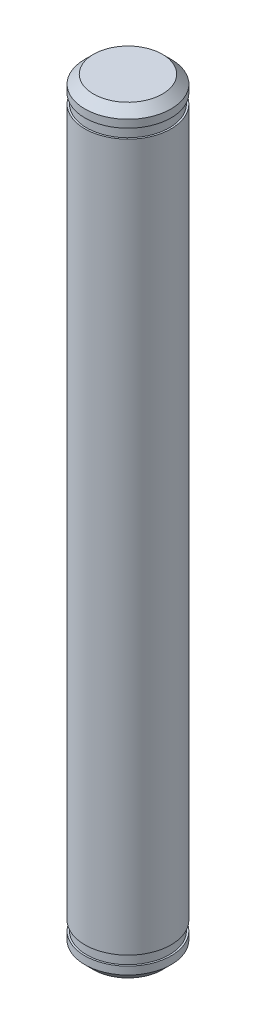
SolidWorks part; units mm, degrees
ref_plane "前视基准面" through (0, 0, 0) normal (0, 0, 1) x (1, 0, 0)
ref_plane "上视基准面" through (0, 0, 0) normal (0, 1, 0) x (1, 0, 0)
ref_plane "右视基准面" through (0, 0, 0) normal (1, 0, 0) x (0, 0, -1)
other "Configuration Table"
sketch "草图1" plane through (0, 0, 0) normal (0, 0, 1) x (1, 0, 0)
  line L0 (0, 61.8249) -> (0, -44.5084) construction
  line L1 (0, 44) -> (5, 44)
  line L2 (5, 44) -> (5, 29)
  line L6 (5, -29) -> (5, -44)
  line L7 (5, -44) -> (0, -44)
  line L8 (0, 0) -> (41.6667, 0) construction
  line L9 (0, 44) -> (0, -44)
  line L10 (5, 29) -> (5, -29)
  dimension "D1" = 5
  dimension "D2" = 5
  dimension "D5" = 88
revolve "旋转1" add sketch "草图1" angle 360 about L9
chamfer "倒角1" distance 1 angle 45 2 edges at (-5, -44, 0) (-5, 44, 0)
ref_plane "基准面1" through (0, 0, 0) normal (0, 1, 0) x (1, 0, 0)
sketch "草图2" plane through (0, 44, 0) normal (0, 1, 0) x (1, 0, 0)
  circle A0 centre (0, 0) radius 5 construction
  circle A1 centre (0, 0) radius 5
  circle A2 centre (0, 0) radius 4.8
  dimension "D1" = 9.6
extrude "切除-拉伸1" cut sketch "草图2" along normal blind 1.1 from offset 3 offset against normal yes
mirror "镜向1" about plane through (0, 0, 0) normal (0, 1, 0) of "切除-拉伸1"
